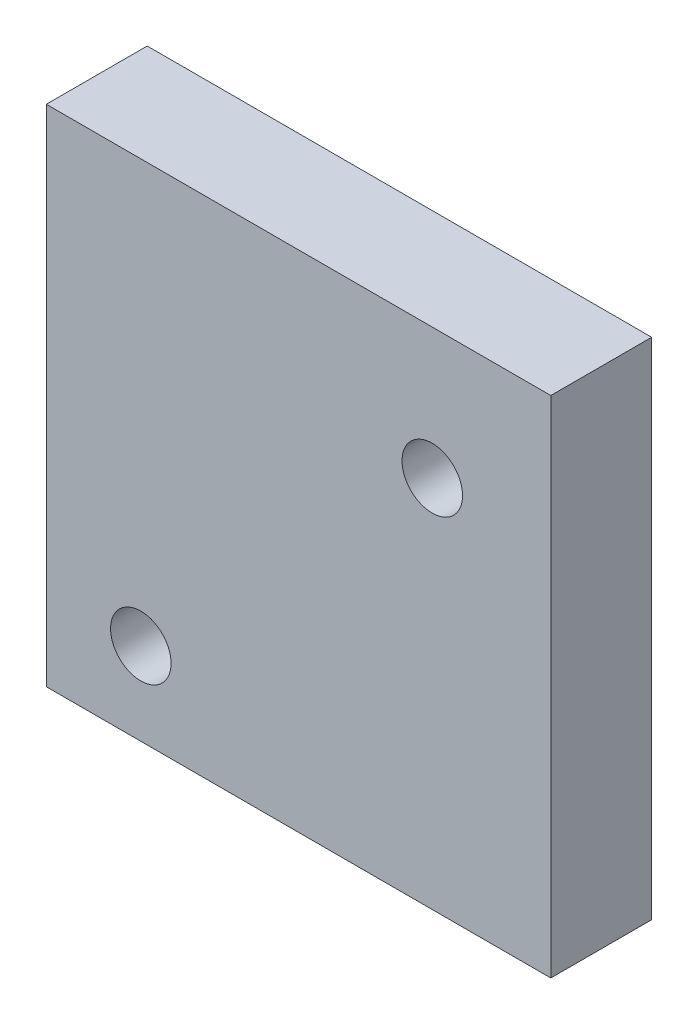
SolidWorks part; units mm, degrees
ref_plane "Front Plane" through (0, 0, 0) normal (0, 0, 1) x (1, 0, 0)
ref_plane "Top Plane" through (0, 0, 0) normal (0, 1, 0) x (1, 0, 0)
ref_plane "Right Plane" through (0, 0, 0) normal (1, 0, 0) x (0, 0, -1)
sketch "Sketch1" plane through (0, 0, 0) normal (0, 0, 1) x (1, 0, 0)
  line L1 (0, 0) -> (100, 0)
  line L2 (0, 0) -> (0, 100)
  line L3 (0, 100) -> (100, 100)
  line L4 (100, 0) -> (100, 100)
  dimension "D1" = 100
  dimension "D2" = 100
extrude "Boss-Extrude1" add sketch "Sketch1" against normal blind 20
hole_wizard "Ø12.0 (12) Diameter Hole1" positions "Sketch2" profile "Sketch3" hole size "Ø12.0" standard "ISO" end condition through all
sketch "Sketch2" plane through (0, 0, 0) normal (0, 0, 1) x (1, 0, 0)
  point P0 (18.731, 16.3608)
  point P2 (76.5076, 74.0583)
sketch "Sketch3" plane through (18.731, 16.3608, 0) normal (1, 0, 0) x (0, -1, 0)
  line L0 (0, 0) -> (0, 20)
  line L1 (0, 20) -> (6, 20)
  line L2 (6, 20) -> (6, 0)
  line L5 (6, 0) -> (0, 0)
  line L11 (0, -6.35) -> (0, 107.95) construction
  dimension "Thru Hole Dia." = 12
  dimension "Thru Hole Depth" = 20
